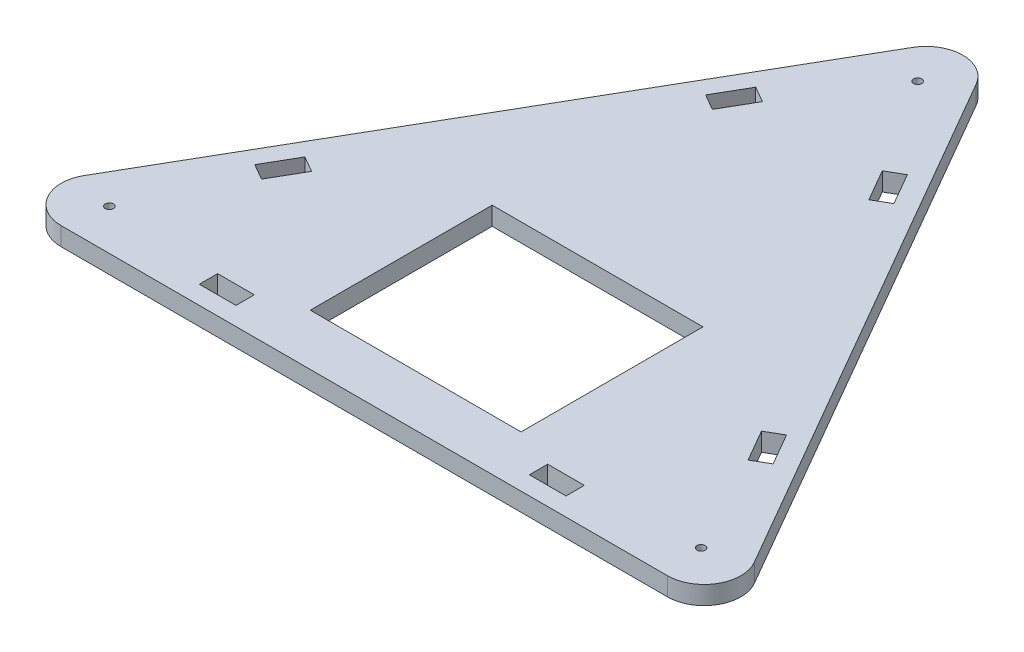
SolidWorks part; units mm, degrees
ref_plane "Front Plane" through (0, 0, 0) normal (0, 0, 1) x (1, 0, 0)
ref_plane "Top Plane" through (0, 0, 0) normal (0, 1, 0) x (1, 0, 0)
ref_plane "Right Plane" through (0, 0, 0) normal (1, 0, 0) x (0, 0, -1)
sketch "Sketch1" plane through (0, 0, 0) normal (0, 1, 0) x (1, 0, 0)
  line L1 (0, 146.647) -> (-127, -73.3235)
  line L2 (-127, -73.3235) -> (127, -73.3235)
  line L3 (127, -73.3235) -> (0, 146.647)
  circle A0 centre (0, 0) radius 73.3235 construction
  dimension "D1" = 254
extrude "Boss-Extrude1" add sketch "Sketch1" along normal blind 6.35
sketch "Sketch2" plane through (0, 6.35, 0) normal (0, 1, 0) x (1, 0, 0)
  line L0 (0, -59.3535) -> (0, -73.3235)
  line L1 (-82.55, -73.3235) -> (82.55, -73.3235)
  line L2 (-82.55, -73.3235) -> (-82.55, -59.3535)
  line L3 (-82.55, -59.3535) -> (82.55, -59.3535)
  line L4 (82.55, -73.3235) -> (82.55, -59.3535)
  line L5 (-127, -73.3235) -> (127, -73.3235) construction
  line L6 (0, -55.5435) -> (0, 7.4565)
  line L7 (-36.5, 7.4565) -> (36.5, 7.4565)
  line L8 (-36.5, 7.4565) -> (-36.5, -55.5435)
  line L9 (-36.5, -55.5435) -> (36.5, -55.5435)
  line L10 (36.5, 7.4565) -> (36.5, -55.5435)
  line L11 (-63.5, 36.6617) -> (-51.4016, 29.6767)
  line L12 (-104.775, -34.8287) -> (-22.225, 108.1521)
  line L13 (-104.775, -34.8287) -> (-92.6766, -41.8137)
  line L14 (-92.6766, -41.8137) -> (-10.1266, 101.1671)
  line L15 (-22.225, 108.1521) -> (-10.1266, 101.1671)
  line L16 (63.5, 36.6617) -> (51.4016, 29.6767)
  line L17 (22.225, 108.1521) -> (104.775, -34.8287)
  line L18 (22.225, 108.1521) -> (10.1266, 101.1671)
  line L19 (10.1266, 101.1671) -> (92.6766, -41.8137)
  line L20 (104.775, -34.8287) -> (92.6766, -41.8137)
  line L23 (0, 146.647) -> (-127, -73.3235) construction
  line L24 (127, -73.3235) -> (0, 146.647) construction
  line L25 (-104.775, -34.8287) -> (-82.55, -73.3235)
  line L26 (104.775, -34.8287) -> (82.55, -73.3235)
  line L27 (-22.225, 108.1521) -> (22.225, 108.1521)
  circle A0 centre (-102.4613, -59.1561) radius 1.4224
  circle A1 centre (102.4613, -59.1561) radius 1.4224
  circle A2 centre (0, 118.3121) radius 1.4224
  dimension "D11" = 2.8448
  dimension "D13" = 2.8448
  dimension "D15" = 2.8448
  dimension "D1" = 165.1
  dimension "D2" = 13.97
  dimension "D3" = 63
  dimension "D4" = 73
  dimension "D5" = 3.81
  dimension "D6" = 165.1
  dimension "D7" = 13.97
  dimension "D8" = 165.1
  dimension "D9" = 13.97
  dimension "D10" = 10.16
  dimension "D12" = 10.16
  dimension "D14" = 10.16
extrude "Cut-Extrude2" cut sketch "Sketch2" against normal through all contours L8 L9 L6 L7 | L10 L7 L6 L9 | A2 | A0 | A1
fillet "Fillet1" radius 12.7 3 edges at (-127, 3.175, 73.3235) (0, 3.175, -146.647) (127, 3.175, 73.3235)
sketch "Sketch3" plane through (0, 6.35, 0) normal (0, 1, 0) x (1, 0, 0)
  line L0 (-10.9985, 127.597) -> (-116.0015, -54.2735) construction
  line L1 (116.0015, -54.2735) -> (10.9985, 127.597) construction
  line L2 (-105.003, -73.3235) -> (105.003, -73.3235) construction
  line B0 (58.0007, 33.4867) -> (52.5015, 30.3117)
  line B1 (96.9515, -46.6779) -> (102.4507, -43.5029)
  line B2 (96.9515, -46.6779) -> (8.0515, 107.3014)
  line B3 (8.0515, 107.3014) -> (13.5507, 110.4764)
  line B4 (102.4507, -43.5029) -> (13.5507, 110.4764)
  line B5 (89.7507, -21.5059) -> (84.2515, -24.6809)
  line B6 (89.7507, -21.5059) -> (83.4007, -10.5073)
  line B7 (83.4007, -10.5073) -> (77.9015, -13.6823)
  line B8 (84.2515, -24.6809) -> (77.9015, -13.6823)
  line B9 (32.6007, 77.4808) -> (27.1015, 74.3058)
  line B10 (32.6007, 77.4808) -> (26.2507, 88.4794)
  line B11 (26.2507, 88.4794) -> (20.7515, 85.3044)
  line B12 (27.1015, 74.3058) -> (20.7515, 85.3044)
  line B13 (102.4507, -43.5029) -> (107.95, -40.3279)
  line B14 (102.4507, -43.5029) -> (13.5507, 110.4764)
  line B15 (13.5507, 110.4764) -> (19.05, 113.6514)
  line B16 (107.95, -40.3279) -> (19.05, 113.6514)
  line B17 (0, -66.9735) -> (0, -60.6235)
  line B18 (-88.9, -60.6235) -> (-88.9, -66.9735)
  line B19 (-88.9, -60.6235) -> (88.9, -60.6235)
  line B20 (88.9, -60.6235) -> (88.9, -66.9735)
  line B21 (-88.9, -66.9735) -> (88.9, -66.9735)
  line B22 (-63.5, -66.9735) -> (-63.5, -60.6235)
  line B23 (-63.5, -66.9735) -> (-50.8, -66.9735)
  line B24 (-50.8, -66.9735) -> (-50.8, -60.6235)
  line B25 (-63.5, -60.6235) -> (-50.8, -60.6235)
  line B26 (50.8, -66.9735) -> (50.8, -60.6235)
  line B27 (50.8, -66.9735) -> (63.5, -66.9735)
  line B28 (63.5, -66.9735) -> (63.5, -60.6235)
  line B29 (50.8, -60.6235) -> (63.5, -60.6235)
  line B30 (-88.9, -66.9735) -> (-88.9, -73.3235)
  line B31 (-88.9, -66.9735) -> (88.9, -66.9735)
  line B32 (88.9, -66.9735) -> (88.9, -73.3235)
  line B33 (-88.9, -73.3235) -> (88.9, -73.3235)
  line B34 (-58.0007, 33.4867) -> (-52.5015, 30.3117)
  line B35 (-8.0515, 107.3014) -> (-13.5507, 110.4764)
  line B36 (-8.0515, 107.3014) -> (-96.9515, -46.6779)
  line B37 (-96.9515, -46.6779) -> (-102.4507, -43.5029)
  line B38 (-13.5507, 110.4764) -> (-102.4507, -43.5029)
  line B39 (-26.2507, 88.4794) -> (-20.7515, 85.3044)
  line B40 (-26.2507, 88.4794) -> (-32.6007, 77.4808)
  line B41 (-32.6007, 77.4808) -> (-27.1015, 74.3058)
  line B42 (-20.7515, 85.3044) -> (-27.1015, 74.3058)
  line B43 (-83.4007, -10.5073) -> (-77.9015, -13.6823)
  line B44 (-83.4007, -10.5073) -> (-89.7507, -21.5059)
  line B45 (-89.7507, -21.5059) -> (-84.2515, -24.6809)
  line B46 (-77.9015, -13.6823) -> (-84.2515, -24.6809)
  line B47 (-13.5507, 110.4764) -> (-19.05, 113.6514)
  line B48 (-13.5507, 110.4764) -> (-102.4507, -43.5029)
  line B49 (-102.4507, -43.5029) -> (-107.95, -40.3279)
  line B50 (-19.05, 113.6514) -> (-107.95, -40.3279)
sketch_block_instance "Block3-1"
sketch_block "Block3" parameters "D1"=177.8, "D2"=6.35, "D3"=25.4, "D4"=25.4, "D5"=12.7, "D6"=12.7, "D7"=6.35
sketch_block_instance "Block3-2"
sketch_block_instance "Block3-3"
extrude "Cut-Extrude3" cut sketch "Sketch3" against normal through all contours B38 B41 B36 B39 | B38 B45 B36 B43 | B21 B24 B19 B22 | B21 B28 B19 B26 | B4 B7 B2 B5 | B4 B11 B2 B9
